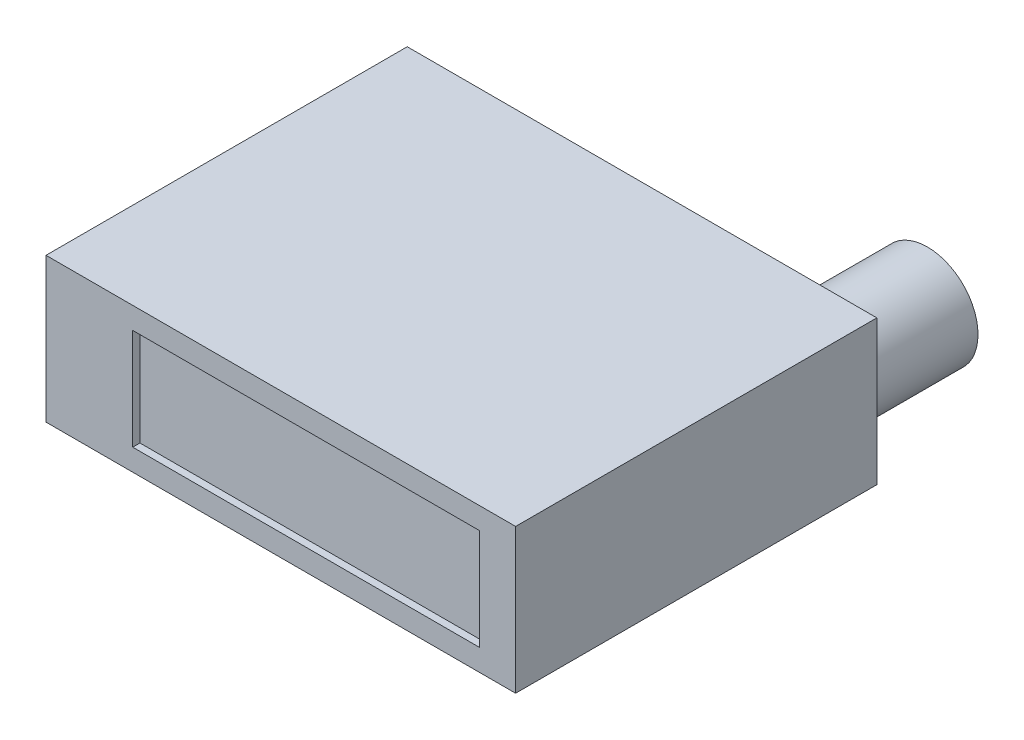
SolidWorks part; units mm, degrees
ref_plane "Front Plane" through (0, 0, 0) normal (0, 0, 1) x (1, 0, 0)
ref_plane "Top Plane" through (0, 0, 0) normal (0, 1, 0) x (1, 0, 0)
ref_plane "Right Plane" through (0, 0, 0) normal (1, 0, 0) x (0, 0, -1)
sketch "Sketch2" plane through (0, 0, 0) normal (0, 1, 0) x (1, 0, 0)
  line L1 (-32.5, 25) -> (32.5, 25)
  line L2 (-32.5, 25) -> (-32.5, -25)
  line L3 (-32.5, -25) -> (32.5, -25)
  line L4 (32.5, 25) -> (32.5, -25)
  line L5 (-32.5, 25) -> (32.5, -25) construction
  line L6 (-32.5, -25) -> (32.5, 25) construction
  point P0 (0, 0)
  dimension "D1" = 65
  dimension "D2" = 50
extrude "Boss-Extrude1" add sketch "Sketch2" along normal blind 20
sketch "Sketch3" plane through (0, 0, -25) normal (0, 0, -1) x (-1, 0, 0)
  line L0 (-32.5, 10) -> (32.5, 10) construction
  line L1 (-32.5, 20) -> (-32.5, 0) construction
  line L2 (32.5, 20) -> (32.5, 0) construction
  circle A0 centre (-24.5, 10) radius 7
  dimension "D1" = 14
  dimension "D2" = 57
extrude "Boss-Extrude2" add sketch "Sketch3" along normal blind 15
sketch "Sketch4" plane through (0, 0, 25) normal (0, 0, 1) x (1, 0, 0)
  line L0 (-32.5, 10) -> (32.5, 10) construction
  line L1 (-32.5, 20) -> (-32.5, 0) construction
  line L2 (32.5, 20) -> (32.5, 0) construction
  line L4 (-20.5, 17) -> (27.5, 17)
  line L5 (-20.5, 17) -> (-20.5, 3)
  line L6 (-20.5, 3) -> (27.5, 3)
  line L7 (27.5, 17) -> (27.5, 3)
  line L8 (-20.5, 17) -> (27.5, 3) construction
  line L9 (-20.5, 3) -> (27.5, 17) construction
  point P6 (3.5, 10)
  dimension "D1" = 12
  dimension "D2" = 48
  dimension "D3" = 14
extrude "Cut-Extrude1" cut sketch "Sketch4" against normal blind 1
